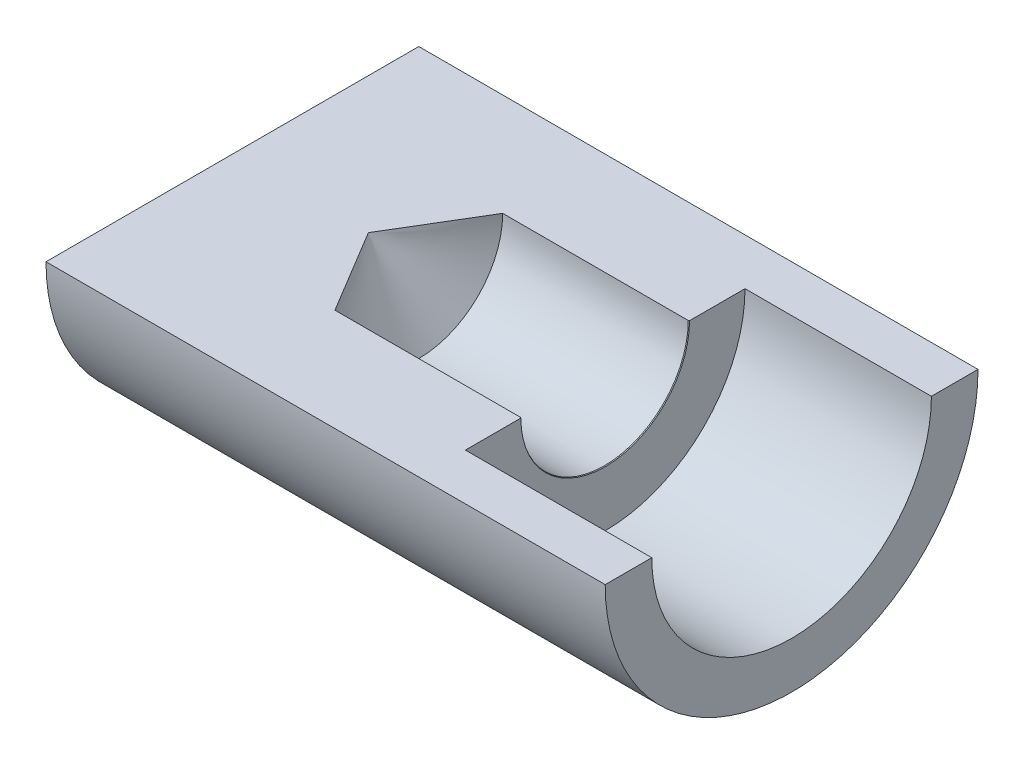
SolidWorks part; units mm, degrees
ref_plane "Plan de face" through (0, 0, 0) normal (0, 0, 1) x (1, 0, 0)
ref_plane "Plan de dessus" through (0, 0, 0) normal (0, 1, 0) x (1, 0, 0)
ref_plane "Plan de droite" through (0, 0, 0) normal (1, 0, 0) x (0, 0, -1)
sketch "Esquisse1" plane through (0, 0, 0) normal (0, 0, 1) x (1, 0, 0)
  line L0 (0, 0) -> (51.7301, 0) construction
  line L1 (0, 0) -> (0, 10)
  line L2 (0, 10) -> (30, 10)
  line L3 (30, 10) -> (30, 0)
  line L4 (0, 0) -> (30, 0)
  dimension "D1" = 30
  dimension "D2" = 10
revolve "Révolution2" add sketch "Esquisse1" angle 360 about L0
hole_wizard "Chambrage pour vis à tête hexagonale M81" positions "Esquisse3D1" profile "Esquisse2" counterbore size "M8" standard "ISO"
sketch3d "Esquisse3D1"
  circle A0 centre (30, 0, 0) radius 10 construction
  point P0 (30, 0, 0)
  point P6 (20, 0, 0)
sketch "Esquisse2" plane through (30, 0, 0) normal (0, 1, 0) x (0, 0, -1)
  line L0 (0, 0) -> (0, 22.7039)
  line L1 (0, 22.7039) -> (4.5, 20)
  line L2 (4.5, 20) -> (4.5, 10.0433)
  line L3 (4.5, 10.0433) -> (4.525, 10)
  line L4 (4.525, 10) -> (7.5, 10)
  line L5 (7.5, 10) -> (7.5, 0)
  line L6 (7.5, 0) -> (0, 0)
  line L9 (-4.5, 10.0433) -> (-4.525, 10) construction
  line L10 (0, 22.7039) -> (-4.5, 20) construction
  line L11 (0, -6.35) -> (0, 107.95) construction
  dimension "Diamètre du perçage" = 9
  dimension "Profondeur du perçage" = 20
  dimension "Diamètre du chambrage" = 15
  dimension "Profondeur du chambrage" = 10
  dimension "Diamètre du fraisage milieu" = 9.05
  dimension "Angle du fraisage milieu" = 60
  dimension "Angle de pointe" = 118
sketch "Esquisse3" plane through (30, 0, 0) normal (1, 0, 0) x (0, 0, -1)
  line L1 (-16.5091, 12) -> (15.4909, 12)
  line L2 (-16.5091, 12) -> (-16.5091, 0)
  line L3 (-16.5091, 0) -> (15.4909, 0)
  line L4 (15.4909, 12) -> (15.4909, 0)
  dimension "D1" = 12
  dimension "D2" = 32
extrude "Enlèv. mat.-Extru.1" cut sketch "Esquisse3" against normal through all
